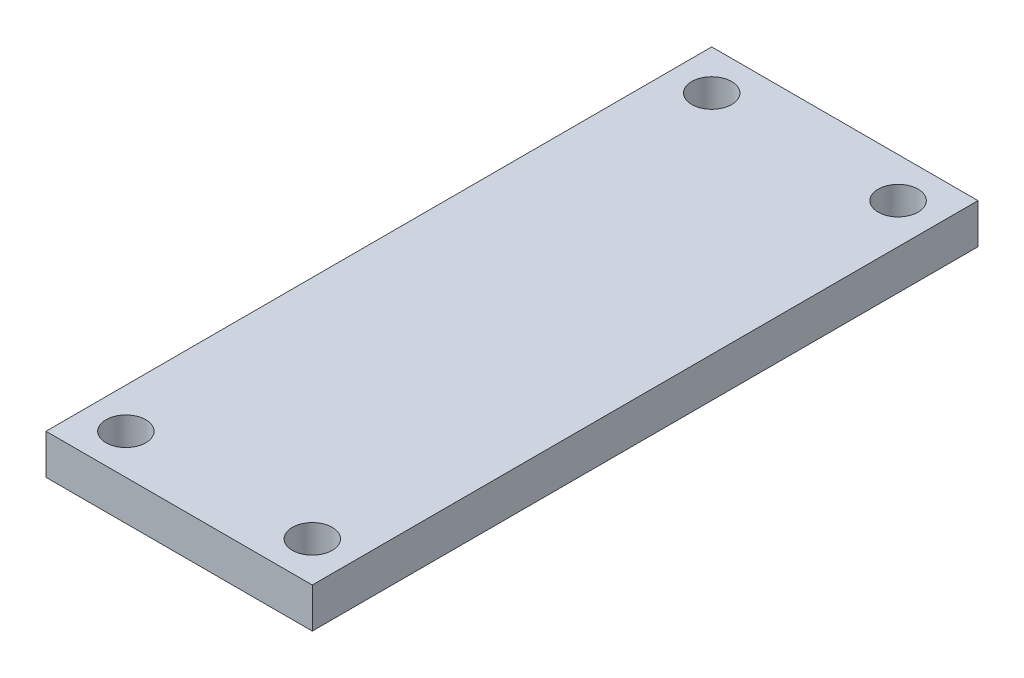
SolidWorks part; units mm, degrees
ref_plane "Plano frontal" through (0, 0, 0) normal (0, 0, 1) x (1, 0, 0)
ref_plane "Plano superior" through (0, 0, 0) normal (0, 1, 0) x (1, 0, 0)
ref_plane "Plano direito" through (0, 0, 0) normal (1, 0, 0) x (0, 0, -1)
sketch "Sketch1" plane through (0, 0, 0) normal (0, 1, 0) x (1, 0, 0)
  line L1 (-10, -25) -> (10, -25)
  line L2 (-10, -25) -> (-10, 25)
  line L3 (-10, 25) -> (10, 25)
  line L4 (10, -25) -> (10, 25)
  line L5 (-10, -25) -> (10, 25) construction
  line L6 (-10, 25) -> (10, -25) construction
  point P0 (0, 0)
  dimension "D1" = 20
  dimension "D2" = 50
extrude "Boss-Extrude1" add sketch "Sketch1" along normal mid plane 3 contours L4 L3 L2 L1
sketch "Sketch2" plane through (0, 1.5, 0) normal (0, 1, 0) x (1, 0, 0)
  line L0 (-10, -25) -> (-10, 25) construction
  line L1 (-10, -25) -> (10, -25) construction
  line L2 (10, -25) -> (10, 25) construction
  line L3 (-10, 25) -> (10, 25) construction
  circle A0 centre (-7, -22) radius 1.5
  circle A1 centre (7, -22) radius 1.5
  circle A2 centre (7, 22) radius 1.5
  circle A3 centre (-7, 22) radius 1.5
  point P12 (0, 0)
  point P15 (0, 0)
  point P18 (0, 0)
  point P19 (0, 0)
  dimension "D1" = 3
  dimension "D4" = 3
  dimension "D5" = 3
  dimension "D6" = 3
  dimension "D2" = 3
  dimension "D3" = 3
  dimension "D7" = 3
  dimension "D8" = 3
extrude "Cut-Extrude1" cut sketch "Sketch2" against normal up to next
equation "\"D4@Sketch2\"=\"D1@Sketch2\""
equation "\"D5@Sketch2\"=\"D1@Sketch2\""
equation "\"D6@Sketch2\"=\"D1@Sketch2\""
equation "\"D8@Sketch2\"=\"D3@Sketch2\""
